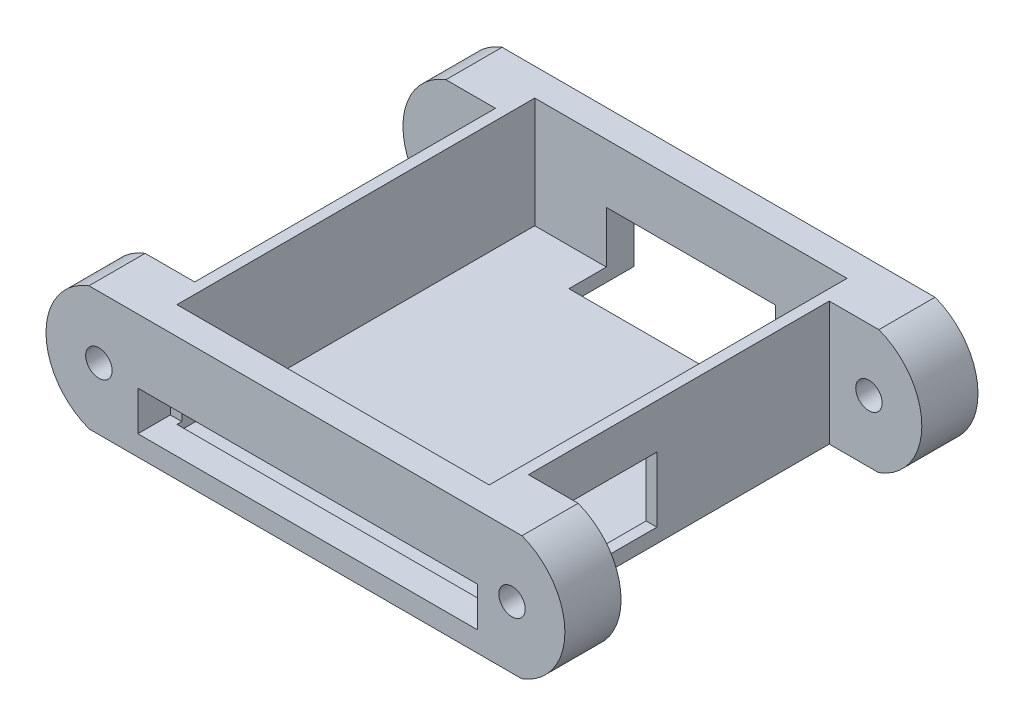
SolidWorks part; units mm, degrees
ref_plane "Front Plane" through (0, 0, 0) normal (0, 0, 1) x (1, 0, 0)
ref_plane "Top Plane" through (0, 0, 0) normal (0, 1, 0) x (1, 0, 0)
ref_plane "Right Plane" through (0, 0, 0) normal (1, 0, 0) x (0, 0, -1)
sketch "Sketch1" plane through (0, 0, 0) normal (0, 1, 0) x (1, 0, 0)
  line L1 (-43.18, 31.75) -> (43.18, 31.75)
  line L2 (-43.18, 31.75) -> (-43.18, -31.75)
  line L3 (-43.18, -31.75) -> (43.18, -31.75)
  line L4 (43.18, 31.75) -> (43.18, -31.75)
  line L5 (-43.18, 31.75) -> (43.18, -31.75) construction
  line L6 (-43.18, -31.75) -> (43.18, 31.75) construction
  point P0 (0, 0)
  dimension "D1" = 86.36
  dimension "D2" = 63.5
extrude "Boss-Extrude1" add sketch "Sketch1" along normal blind 19.05
sketch "Sketch2" plane through (0, 0, 31.75) normal (0, 0, 1) x (1, 0, 0)
  line L0 (-43.18, 19.05) -> (-43.18, 0)
  line L1 (-43.18, 19.05) -> (-33.274, 19.05)
  line L2 (-43.18, 19.05) -> (43.18, 19.05) construction
  line L3 (-43.18, 0) -> (-33.2329, 0)
  line L4 (-43.18, 0) -> (43.18, 0) construction
  line L5 (0, -10.4775) -> (0, 10.4775) construction
  line L6 (43.18, 19.05) -> (43.18, 0)
  line L7 (43.18, 0) -> (33.2329, 0)
  line L8 (43.18, 19.05) -> (33.274, 19.05)
  arc A0 (-33.274, 19.05) -> (-33.2329, 0) centre (-29.718, 9.5326) ccw
  arc A1 (33.274, 19.05) -> (33.2329, 0) centre (29.718, 9.5326) cw
  dimension "D1" = 10.16
  dimension "D3" = 13.462
  dimension "D2" = 3.556
extrude "Cut-Extrude1" cut sketch "Sketch2" against normal blind 63.5
sketch "Sketch3" plane through (0, 19.05, 0) normal (0, 1, 0) x (1, 0, 0)
  line L0 (-39.878, 23.114) -> (-25.654, 23.114)
  line L1 (-39.878, 23.114) -> (-39.878, -23.114)
  line L2 (-25.654, 23.114) -> (-25.654, -23.114)
  line L3 (-39.878, -23.114) -> (-25.654, -23.114)
  line L4 (-39.878, 31.75) -> (-39.878, -31.75) construction
  line L5 (-33.274, -31.75) -> (33.274, -31.75) construction
  line L6 (33.274, 31.75) -> (-33.274, 31.75) construction
  line L7 (0, -10.4775) -> (0, 10.4775) construction
  line L8 (39.878, 23.114) -> (39.878, -23.114)
  line L9 (39.878, -23.114) -> (25.654, -23.114)
  line L10 (25.654, 23.114) -> (25.654, -23.114)
  line L11 (39.878, 23.114) -> (25.654, 23.114)
  dimension "D1" = 14.224
  dimension "D2" = 8.636
  dimension "D3" = 8.636
extrude "Cut-Extrude4" cut sketch "Sketch3" against normal blind 63.5
sketch "Sketch4" plane through (0, 0, 31.75) normal (0, 0, 1) x (1, 0, 0)
  line L1 (-33.2329, 0) -> (33.2329, 0) construction
  line L2 (0, -10.4775) -> (0, 10.4775) construction
  circle A0 centre (-31.75, 9.525) radius 2.032
  arc A1 (-33.274, 19.05) -> (-33.2329, 0) centre (-29.718, 9.5326) ccw construction
  circle A2 centre (31.75, 9.525) radius 2.032
  dimension "D1" = 4.064
  dimension "D2" = 9.525
  dimension "D3" = 2.032
extrude "Cut-Extrude5" cut sketch "Sketch4" against normal blind 63.5
sketch "Sketch6" plane through (0, 19.05, 0) normal (0, 1, 0) x (1, 0, 0)
  line L1 (-24, 27.5) -> (24, 27.5)
  line L2 (-24, 27.5) -> (-24, -27.5)
  line L3 (-24, -27.5) -> (24, -27.5)
  line L4 (24, 27.5) -> (24, -27.5)
  line L5 (-24, 27.5) -> (24, -27.5) construction
  line L6 (-24, -27.5) -> (24, 27.5) construction
  point P0 (0, 0)
  dimension "D1" = 55
  dimension "D2" = 48
extrude "Cut-Extrude6" cut sketch "Sketch6" against normal blind 17
sketch "Sketch7" plane through (25.654, 0, 0) normal (1, 0, 0) x (0, 0, -1)
  line L0 (23.114, 0) -> (-23.114, 0) construction
  line L1 (-18.386, 12.2) -> (-3.386, 12.2)
  line L2 (-18.386, 12.2) -> (-18.386, 2.2)
  line L3 (-18.386, 2.2) -> (-3.386, 2.2)
  line L4 (-3.386, 12.2) -> (-3.386, 2.2)
  line L5 (-18.386, 12.2) -> (-3.386, 2.2) construction
  line L6 (-18.386, 2.2) -> (-3.386, 12.2) construction
  line L8 (23.114, 0) -> (23.114, 19.05) construction
  point P0 (-10.886, 7.2)
  dimension "D1" = 15
  dimension "D2" = 10
  dimension "D3" = 2.2
  dimension "D4" = 26.5
extrude "Cut-Extrude10" cut sketch "Sketch7" against normal blind 17
sketch "Sketch9" plane through (0, 0, -31.75) normal (0, 0, -1) x (-1, 0, 0)
  line L1 (-13, -10) -> (13, -10)
  line L2 (-13, -10) -> (-13, 10)
  line L3 (-13, 10) -> (13, 10)
  line L4 (13, -10) -> (13, 10)
  line L5 (-13, -10) -> (13, 10) construction
  line L6 (-13, 10) -> (13, -10) construction
  point P0 (0, 0)
  dimension "D1" = 20
  dimension "D2" = 26
extrude "Cut-Extrude11" cut sketch "Sketch9" against normal blind 10
sketch "Sketch10" plane through (0, 0, 31.75) normal (0, 0, 1) x (1, 0, 0)
  line L1 (-25.7617, 9.1923) -> (26.4271, 9.1923)
  line L2 (-25.7617, 9.1923) -> (-25.7617, 3.1083)
  line L3 (-25.7617, 3.1083) -> (26.4271, 3.1083)
  line L4 (26.4271, 9.1923) -> (26.4271, 3.1083)
  line L5 (-25.7617, 9.1923) -> (26.4271, 3.1083) construction
  line L6 (-25.7617, 3.1083) -> (26.4271, 9.1923) construction
  point P0 (0.3327, 6.1503)
extrude "Cut-Extrude12" cut sketch "Sketch10" against normal blind 5
